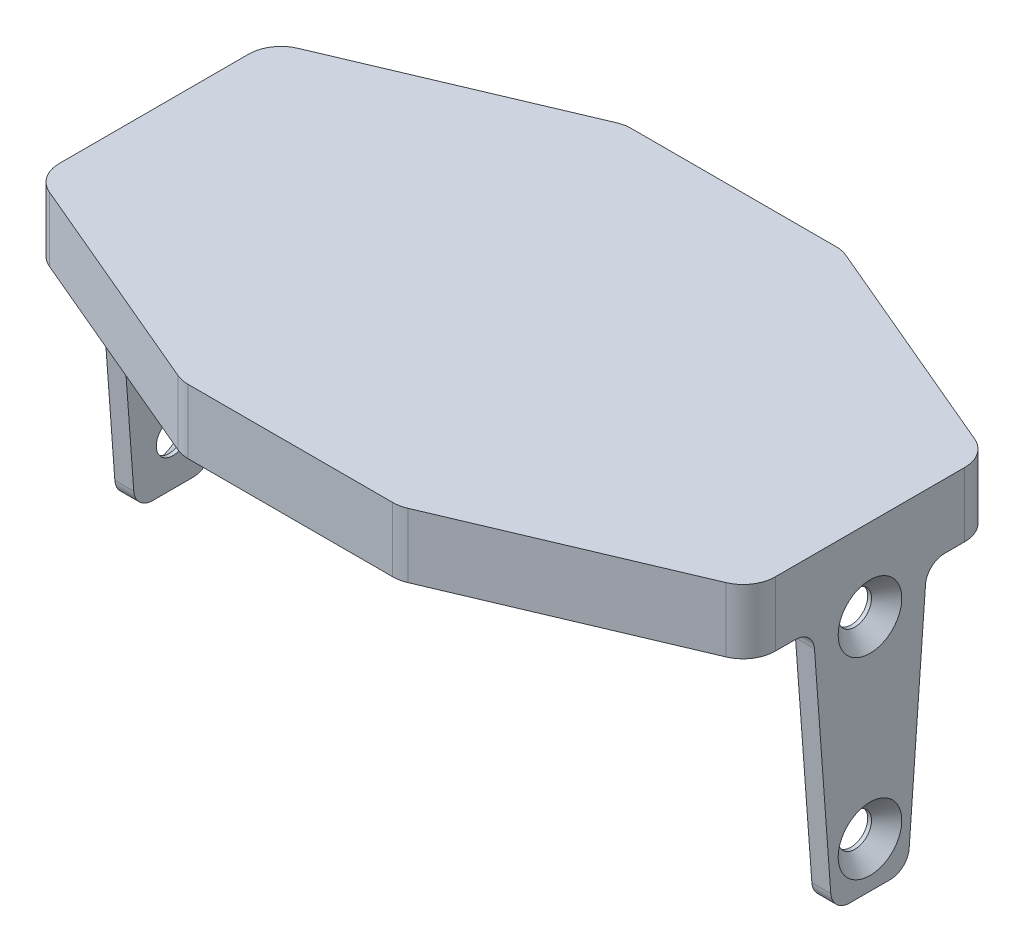
SolidWorks part; units mm, degrees
ref_plane "Front Plane" through (0, 0, 0) normal (0, 0, 1) x (1, 0, 0)
ref_plane "Top Plane" through (0, 0, 0) normal (0, 1, 0) x (1, 0, 0)
ref_plane "Right Plane" through (0, 0, 0) normal (1, 0, 0) x (0, 0, -1)
sketch "Sketch1" plane through (0, 0, 0) normal (0, 1, 0) x (1, 0, 0)
  line L0 (0, 79.6957) -> (0, -81.2336) construction
  line L1 (-87.6652, 0) -> (87.7969, 0) construction
  line L2 (-44.25, -12.5) -> (-44.25, 12.5) construction
  line L3 (-43.4877, 13.6509) -> (-13.9877, 26.1509) construction
  line L4 (-13.5, 26.25) -> (13.5, 26.25) construction
  line L5 (-13.5, -26.25) -> (13.5, -26.25) construction
  line L6 (-43.4877, -13.6509) -> (-13.9877, -26.1509) construction
  line L7 (43.4877, -13.6509) -> (13.9877, -26.1509) construction
  line L8 (44.25, -12.5) -> (44.25, 12.5) construction
  line L9 (43.4877, 13.6509) -> (13.9877, 26.1509) construction
  line L10 (43.6828, 14.1113) -> (14.1828, 26.6113)
  line L11 (-13.5, 26.75) -> (13.5, 26.75)
  line L12 (-43.6828, 14.1113) -> (-14.1828, 26.6113)
  line L13 (-44.75, -12.5) -> (-44.75, 12.5)
  line L14 (-43.6828, -14.1113) -> (-14.1828, -26.6113)
  line L15 (-13.5, -26.75) -> (13.5, -26.75)
  line L16 (43.6828, -14.1113) -> (14.1828, -26.6113)
  line L17 (44.75, -12.5) -> (44.75, 12.5)
  line L18 (44.6581, 16.4132) -> (15.1581, 28.9132)
  line L19 (-13.5, 29.25) -> (13.5, 29.25)
  line L20 (-44.6581, 16.4132) -> (-15.1581, 28.9132)
  line L21 (-47.25, -12.5) -> (-47.25, 12.5)
  line L22 (-44.6581, -16.4132) -> (-15.1581, -28.9132)
  line L23 (-13.5, -29.25) -> (13.5, -29.25)
  line L24 (44.6581, -16.4132) -> (15.1581, -28.9132)
  line L25 (47.25, -12.5) -> (47.25, 12.5)
  arc A0 (-44.25, 12.5) -> (-43.4877, 13.6509) centre (-43, 12.5) cw construction
  arc A1 (-13.9877, 26.1509) -> (-13.5, 26.25) centre (-13.5, 25) cw construction
  arc A2 (-13.9877, -26.1509) -> (-13.5, -26.25) centre (-13.5, -25) ccw construction
  arc A3 (-44.25, -12.5) -> (-43.4877, -13.6509) centre (-43, -12.5) ccw construction
  arc A4 (13.9877, -26.1509) -> (13.5, -26.25) centre (13.5, -25) cw construction
  arc A5 (44.25, -12.5) -> (43.4877, -13.6509) centre (43, -12.5) cw construction
  arc A6 (44.25, 12.5) -> (43.4877, 13.6509) centre (43, 12.5) ccw construction
  arc A7 (13.9877, 26.1509) -> (13.5, 26.25) centre (13.5, 25) ccw construction
  arc A8 (14.1828, 26.6113) -> (13.5, 26.75) centre (13.5, 25) ccw
  arc A9 (-14.1828, 26.6113) -> (-13.5, 26.75) centre (-13.5, 25) cw
  arc A10 (-44.75, 12.5) -> (-43.6828, 14.1113) centre (-43, 12.5) cw
  arc A11 (-44.75, -12.5) -> (-43.6828, -14.1113) centre (-43, -12.5) ccw
  arc A12 (-14.1828, -26.6113) -> (-13.5, -26.75) centre (-13.5, -25) ccw
  arc A13 (14.1828, -26.6113) -> (13.5, -26.75) centre (13.5, -25) cw
  arc A14 (44.75, -12.5) -> (43.6828, -14.1113) centre (43, -12.5) cw
  arc A15 (44.75, 12.5) -> (43.6828, 14.1113) centre (43, 12.5) ccw
  arc A16 (15.1581, 28.9132) -> (13.5, 29.25) centre (13.5, 25) ccw
  arc A17 (-15.1581, 28.9132) -> (-13.5, 29.25) centre (-13.5, 25) cw
  arc A18 (-47.25, 12.5) -> (-44.6581, 16.4132) centre (-43, 12.5) cw
  arc A19 (-47.25, -12.5) -> (-44.6581, -16.4132) centre (-43, -12.5) ccw
  arc A20 (-15.1581, -28.9132) -> (-13.5, -29.25) centre (-13.5, -25) ccw
  arc A21 (15.1581, -28.9132) -> (13.5, -29.25) centre (13.5, -25) cw
  arc A22 (47.25, -12.5) -> (44.6581, -16.4132) centre (43, -12.5) cw
  arc A23 (47.25, 12.5) -> (44.6581, 16.4132) centre (43, 12.5) ccw
  point P20 (-44.25, 0)
  point P21 (0, -26.25)
  point P32 (0, 26.25)
  dimension "D3" = 1.25
  dimension "D4" = 1.25
  dimension "D1" = 25
  dimension "D2" = 50
  dimension "D5" = 27
  dimension "D6" = 86
  dimension "D7" = 0.5
  dimension "D8" = 2.5
extrude "Boss-Extrude1" add sketch "Sketch1" along normal blind 6
sketch "Sketch2" plane through (0, 6, 0) normal (0, 1, 0) x (1, 0, 0)
  line L0 (-44.6581, -16.4132) -> (-15.1581, -28.9132) construction
  line L1 (-13.5, -29.25) -> (13.5, -29.25) construction
  line L2 (15.1581, -28.9132) -> (44.6581, -16.4132) construction
  line L3 (47.25, -12.5) -> (47.25, 12.5) construction
  line L4 (44.6581, 16.4132) -> (15.1581, 28.9132) construction
  line L5 (13.5, 29.25) -> (-13.5, 29.25) construction
  line L6 (-15.1581, 28.9132) -> (-44.6581, 16.4132) construction
  line L7 (-47.25, 12.5) -> (-47.25, -12.5) construction
  line L8 (-44.6581, -16.4132) -> (-15.1581, -28.9132)
  line L9 (-13.5, -29.25) -> (13.5, -29.25)
  line L10 (15.1581, -28.9132) -> (44.6581, -16.4132)
  line L11 (47.25, -12.5) -> (47.25, 12.5)
  line L12 (44.6581, 16.4132) -> (15.1581, 28.9132)
  line L13 (13.5, 29.25) -> (-13.5, 29.25)
  line L14 (-15.1581, 28.9132) -> (-44.6581, 16.4132)
  line L15 (-47.25, 12.5) -> (-47.25, -12.5)
  arc A0 (-15.1581, -28.9132) -> (-13.5, -29.25) centre (-13.5, -25) ccw construction
  arc A1 (13.5, -29.25) -> (15.1581, -28.9132) centre (13.5, -25) ccw construction
  arc A2 (44.6581, -16.4132) -> (47.25, -12.5) centre (43, -12.5) ccw construction
  arc A3 (47.25, 12.5) -> (44.6581, 16.4132) centre (43, 12.5) ccw construction
  arc A4 (15.1581, 28.9132) -> (13.5, 29.25) centre (13.5, 25) ccw construction
  arc A5 (-13.5, 29.25) -> (-15.1581, 28.9132) centre (-13.5, 25) ccw construction
  arc A6 (-44.6581, 16.4132) -> (-47.25, 12.5) centre (-43, 12.5) ccw construction
  arc A7 (-47.25, -12.5) -> (-44.6581, -16.4132) centre (-43, -12.5) ccw construction
  arc A8 (-15.1581, -28.9132) -> (-13.5, -29.25) centre (-13.5, -25) ccw
  arc A9 (13.5, -29.25) -> (15.1581, -28.9132) centre (13.5, -25) ccw
  arc A10 (44.6581, -16.4132) -> (47.25, -12.5) centre (43, -12.5) ccw
  arc A11 (47.25, 12.5) -> (44.6581, 16.4132) centre (43, 12.5) ccw
  arc A12 (15.1581, 28.9132) -> (13.5, 29.25) centre (13.5, 25) ccw
  arc A13 (-13.5, 29.25) -> (-15.1581, 28.9132) centre (-13.5, 25) ccw
  arc A14 (-44.6581, 16.4132) -> (-47.25, 12.5) centre (-43, 12.5) ccw
  arc A15 (-47.25, -12.5) -> (-44.6581, -16.4132) centre (-43, -12.5) ccw
extrude "Boss-Extrude2" add sketch "Sketch2" along normal blind 2.5
sketch "Sketch8" plane through (0, 6, 0) normal (0, -1, 0) x (-1, 0, 0)
  circle A0 centre (40, 10.513) radius 1.25
  circle A1 centre (16.5, 20.4706) radius 1.25
  circle A2 centre (-16.5, -20.4706) radius 1.25
  circle A3 centre (-40, -10.513) radius 1.25
  circle A4 centre (-40, 10.513) radius 1.25
  circle A5 centre (-16.5, 20.4706) radius 1.25
  circle A6 centre (40, -10.513) radius 1.25
  circle A7 centre (16.5, -20.4706) radius 1.25
sketch "Sketch4" plane through (47.25, 0, 0) normal (1, 0, 0) x (0, 0, -1)
  line L0 (-7.5, 0) -> (7.5, 0)
  line L1 (-12.5, 0) -> (12.5, 0) construction
  line L2 (-7.5, 0) -> (-5, -33.7)
  line L3 (-5, -33.7) -> (5, -33.7)
  line L4 (0, 13.6747) -> (0, -27.8237) construction
  line L5 (7.5, 0) -> (5, -33.7)
  point P10 (0, 0)
  point P11 (0, -33.7)
  dimension "D1" = 33.7
  dimension "D2" = 15
  dimension "D3" = 10
extrude "Boss-Extrude4" add sketch "Sketch4" against normal up to surface (2.5 mm away) up to face at (44.75, 3, 0)
sketch "Sketch5" plane through (-47.25, 0, 0) normal (-1, 0, 0) x (0, 0, 1)
  line L0 (7.5, 0) -> (5, -33.7) construction
  line L1 (5, -33.7) -> (-5, -33.7) construction
  line L2 (-5, -33.7) -> (-7.5, 0) construction
  line L3 (7.5, 0) -> (5, -33.7)
  line L4 (5, -33.7) -> (-5, -33.7)
  line L5 (-5, -33.7) -> (-7.5, 0)
  line L6 (-7.5, 0) -> (7.5, 0)
extrude "Boss-Extrude5" add sketch "Sketch5" against normal up to surface (2.5 mm away) up to face at (-44.75, 3, 0)
fillet "Fillet1" radius 2.5 8 edges at (-46, 0, 7.5) (-46, -33.7, 5) (-46, -33.7, -5) (-46, 0, -7.5) (46, -33.7, 5) (46, -33.7, -5) (46, 0, -7.5) (46, 0, 7.5)
sketch "Sketch6" plane through (47.25, 0, 0) normal (1, 0, 0) x (0, 0, -1)
  line L0 (-12.5, 8.5) -> (12.5, 8.5) construction
  line L1 (0, 11.3832) -> (0, -47.1044) construction
  circle A0 centre (0, -2.3) radius 2.2
  circle A1 centre (0, -27.7) radius 2.2
  dimension "D3" = 4.4
  dimension "D4" = 4.4
  dimension "D1" = 10.8
  dimension "D2" = 25.4
extrude "Cut-Extrude1" cut sketch "Sketch6" against normal through all
chamfer "Chamfer1" distance 2 angle 45 4 edges at (-47.25, -27.7, -2.2) (-47.25, -2.3, -2.2) (47.25, -27.7, -2.2) (47.25, -2.3, -2.2)
extrude "Boss-Extrude6" add sketch "Sketch8" along normal blind 2.5
sketch "Sketch10" plane through (0, 6, 0) normal (0, -1, 0) x (-1, 0, 0)
  line L0 (0, -48.413) -> (0, 62.7049) construction
  line L1 (6.25, -2.5) -> (8.75, -2.5)
  line L2 (6.25, -2.5) -> (6.25, 2.5)
  line L3 (6.25, 2.5) -> (8.75, 2.5)
  line L4 (8.75, -2.5) -> (8.75, 2.5)
  line L5 (97.0995, 0) -> (-98.7388, 0) construction
  dimension "D1" = 5
  dimension "D2" = 2.5
  dimension "D3" = 6.25
extrude "Boss-Extrude8" add sketch "Sketch10" along normal blind 7.5
sketch "Sketch11" plane through (-6.25, 0, 0) normal (-1, 0, 0) x (0, 0, 1)
  line L0 (-2.5, -1.5) -> (-2.5, 6) construction
  line L1 (2.5, -1.5) -> (-2.5, -1.5)
  line L2 (2.5, -1.5) -> (2.5, 1)
  line L3 (2.5, 1) -> (-2.5, 1)
  line L4 (-2.5, -1.5) -> (-2.5, 1)
  dimension "D1" = 2.5
extrude "Boss-Extrude9" add sketch "Sketch11" against normal blind 15
fillet "Fillet2" radius 1 8 edges at (-7.5, 6, -2.5) (-6.25, 6, 0) (-7.5, 6, 2.5) (-8.75, 6, 0) (8.75, 1, 0) (8.75, -1.5, 0) (-8.75, -1.5, 0) (-6.25, 1, 0)
